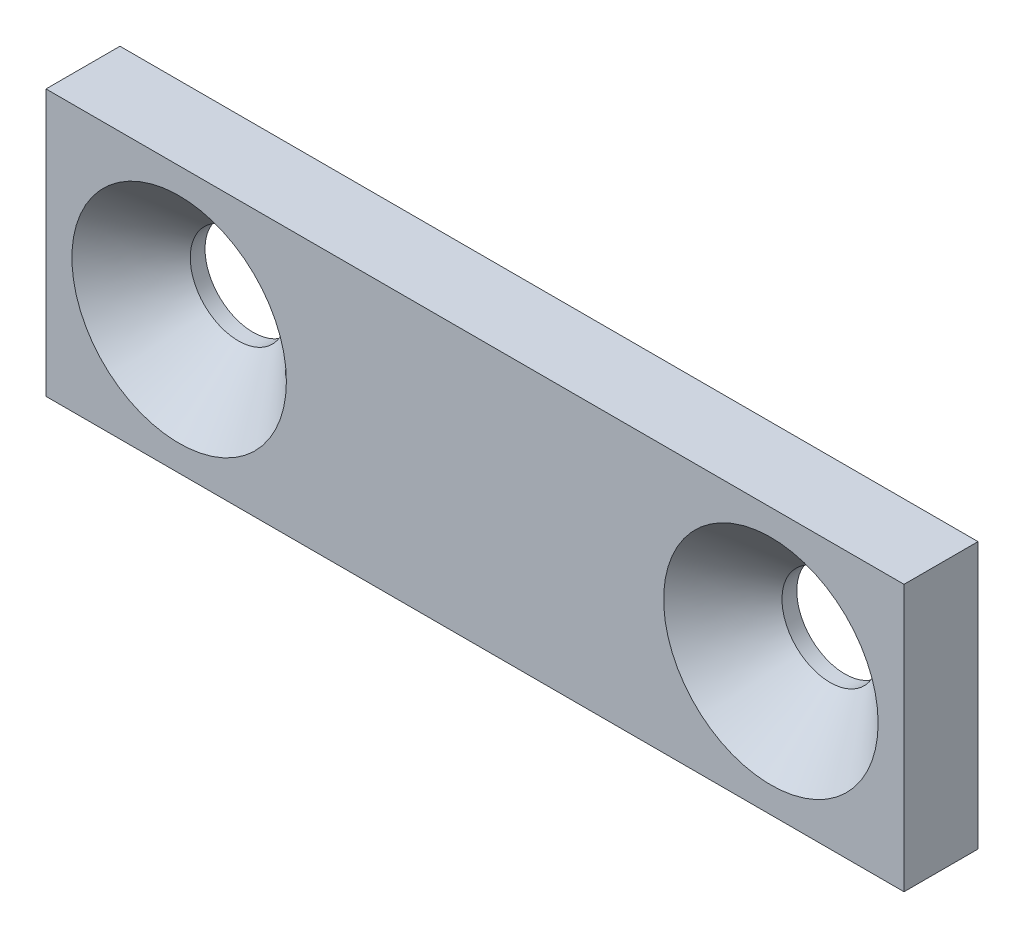
SolidWorks part; units mm, degrees
material "1.0037 (S235JR)"
ref_plane "Front Plane" through (0, 0, 0) normal (0, 0, 1) x (1, 0, 0)
ref_plane "Top Plane" through (0, 0, 0) normal (0, 1, 0) x (1, 0, 0)
ref_plane "Right Plane" through (0, 0, 0) normal (1, 0, 0) x (0, 0, -1)
sketch "Esquisse1" plane through (0, 0, 0) normal (0, 0, 1) x (1, 0, 0)
  line L1 (-29, 9) -> (29, 9)
  line L2 (-29, 9) -> (-29, -9)
  line L3 (-29, -9) -> (29, -9)
  line L4 (29, 9) -> (29, -9)
  line L5 (-29, 9) -> (29, -9) construction
  line L6 (-29, -9) -> (29, 9) construction
  point P0 (0, 0)
  dimension "D1" = 18
  dimension "D2" = 58
extrude "Boss.-Extru.1" add sketch "Esquisse1" along normal blind 5
hole_wizard "Fraisage pour vis à tête fraisée à 6 pans creux M61" positions "Esquisse2" profile "Esquisse3" countersink size "M6" standard "ISO" end condition through all
sketch "Esquisse2" plane through (0, 0, 5) normal (0, 0, 1) x (1, 0, 0)
  line L0 (29, -9) -> (29, 9) construction
  line L1 (-29, -9) -> (29, -9) construction
  point P0 (20, 0)
  dimension "D1" = 9
  dimension "D2" = 9
sketch "Esquisse3" plane through (20, 0, 5) normal (1, 0, 0) x (0, -1, 0)
  line L0 (0, 0) -> (0, 5)
  line L1 (0, 5) -> (3.25, 5)
  line L2 (3.25, 5) -> (3.25, 4)
  line L3 (3.25, 4) -> (7.25, 0)
  line L5 (7.25, 0) -> (0, 0)
  line L6 (-3.25, 4) -> (-7.25, 0) construction
  line L11 (0, -6.35) -> (0, 107.95) construction
  dimension "Diamètre du perçage jusqu'au prochain" = 6.5
  dimension "Profondeur du perçage jusqu'au prochain" = 5
  dimension "Diamètre du fraisage entrant" = 14.5
  dimension "Angle du fraisage entrant" = 90
pattern_linear "Répétition linéaire1" count 2 spacing 40 along (-1, 0, 0) of "Fraisage pour vis à tête fraisée à 6 pans creux M61"
